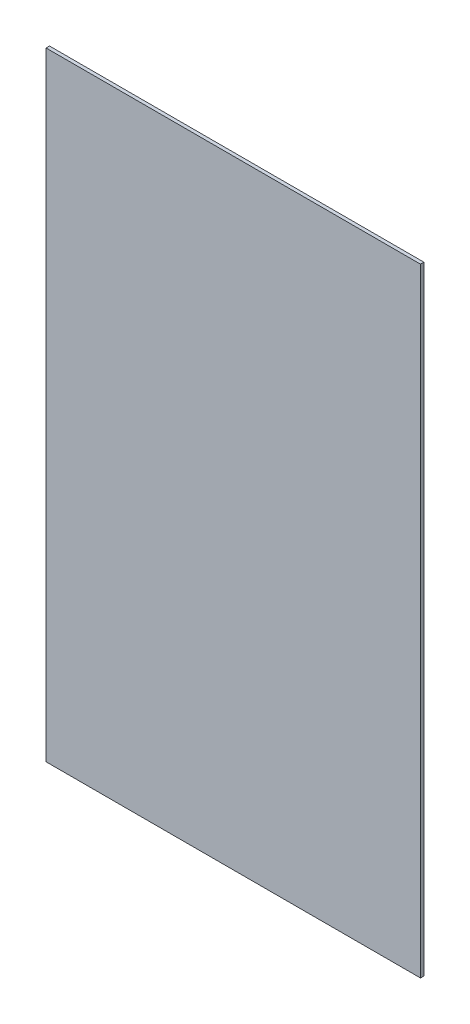
SolidWorks part; units mm, degrees
material "Acrylic (Medium-high impact)"
ref_plane "Front Plane" through (0, 0, 0) normal (0, 0, 1) x (1, 0, 0)
ref_plane "Top Plane" through (0, 0, 0) normal (0, 1, 0) x (1, 0, 0)
ref_plane "Right Plane" through (0, 0, 0) normal (1, 0, 0) x (0, 0, -1)
sketch "Sketch1" plane through (0, 0, 0) normal (0, 0, 1) x (1, 0, 0)
  line L1 (0, 0) -> (346.1419, 0)
  line L2 (0, 0) -> (0, 571.5)
  line L3 (0, 571.5) -> (346.1419, 571.5)
  line L4 (346.1419, 0) -> (346.1419, 571.5)
  point P5 (86.36, 571.5)
  dimension "D1" = 571.5
  dimension "D2" = 346.1419
extrude "Boss-Extrude1" add sketch "Sketch1" along normal blind 3.175
